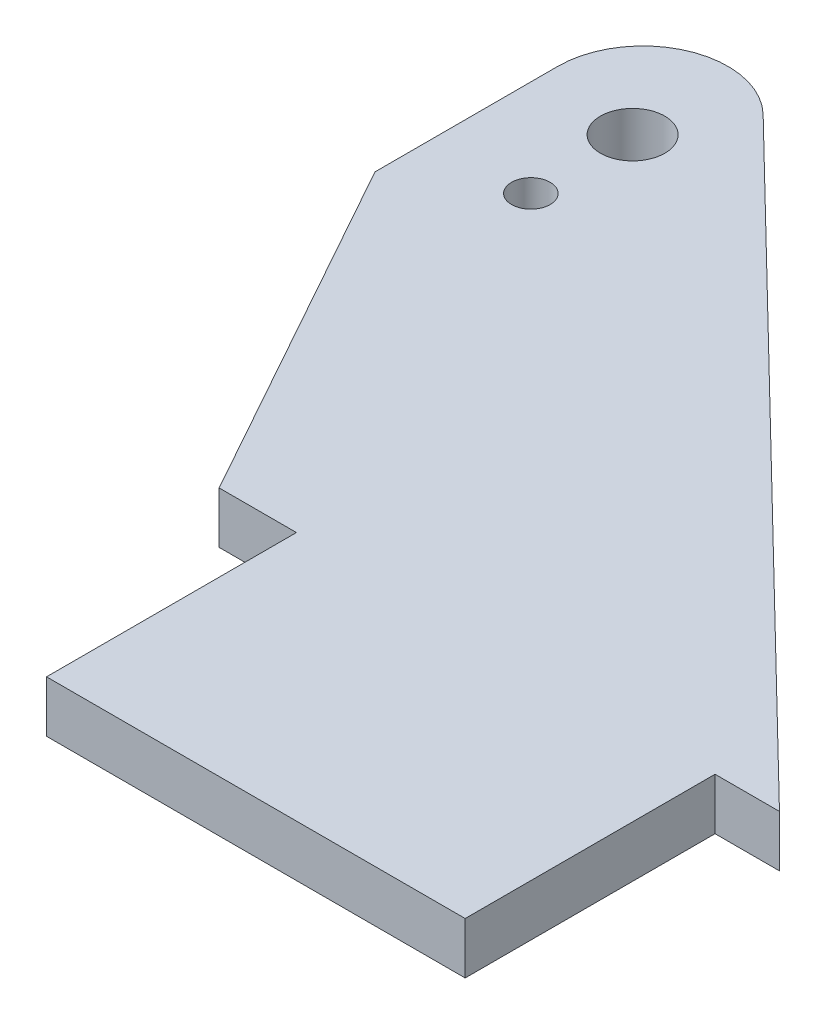
SolidWorks part; units mm, degrees
ref_plane "Front Plane" through (0, 0, 0) normal (0, 0, 1) x (1, 0, 0)
ref_plane "Top Plane" through (0, 0, 0) normal (0, 1, 0) x (1, 0, 0)
ref_plane "Right Plane" through (0, 0, 0) normal (1, 0, 0) x (0, 0, -1)
sketch "Sketch1" plane through (0, 0, 0) normal (0, 1, 0) x (1, 0, 0)
  line L0 (0, 0) -> (8.255, 0)
  line L1 (8.255, 0) -> (8.255, 4.9276)
  line L2 (8.255, 4.9276) -> (9.525, 4.9276)
  line L3 (9.525, 4.9276) -> (-2.5391, 16.6699)
  line L4 (0, 0) -> (0, 4.9276)
  line L5 (0, 4.9276) -> (-1.524, 4.9276)
  line L6 (-1.524, 4.9276) -> (-5.3848, 11.8618)
  line L7 (-3.7084, 17.145) -> (19.1352, 17.145) construction
  line L8 (-5.3848, 11.8618) -> (-5.3848, 15.4686)
  arc A0 (-5.3848, 15.4686) -> (-2.5391, 16.6699) centre (-3.7084, 15.4686) cw
  dimension "D1" = 8.255
  dimension "D2" = 4.9276
  dimension "D3" = 1.524
  dimension "D4" = 17.145
  dimension "D5" = 14.9098
  dimension "D6" = 1.27
  dimension "D7" = 11.8618
  dimension "D8" = 3.6068
extrude "Boss-Extrude1" add sketch "Sketch1" along normal blind 1.016
sketch "Sketch2" plane through (0, 1.016, 0) normal (0, 1, 0) x (1, 0, 0)
  line L0 (-3.4798, 13.4112) -> (-0.9057, 13.4112) construction
  line L1 (-3.4798, 14.4018) -> (-2.1032, 14.4018) construction
  line L2 (-3.4798, 15.6718) -> (-6.2146, 15.6718) construction
  line L3 (-3.7084, 17.145) -> (-7.0668, 17.145) construction
  line L4 (-4.1148, 15.0368) -> (-4.1148, 13.9176) construction
  line L5 (-5.3848, 15.4686) -> (-5.3848, 11.8618) construction
  circle A0 centre (-3.4798, 15.0368) radius 0.635
  circle A1 centre (-3.4798, 13.0302) radius 0.381
  arc A2 (-2.5391, 16.6699) -> (-5.3848, 15.4686) centre (-3.7084, 15.4686) ccw construction
  dimension "D1" = 0.762
  dimension "D3" = 1.27
  dimension "D2" = 0.9906
  dimension "D4" = 1.4732
  dimension "D5" = 1.27
extrude "Cut-Extrude1" cut sketch "Sketch2" against normal through all
